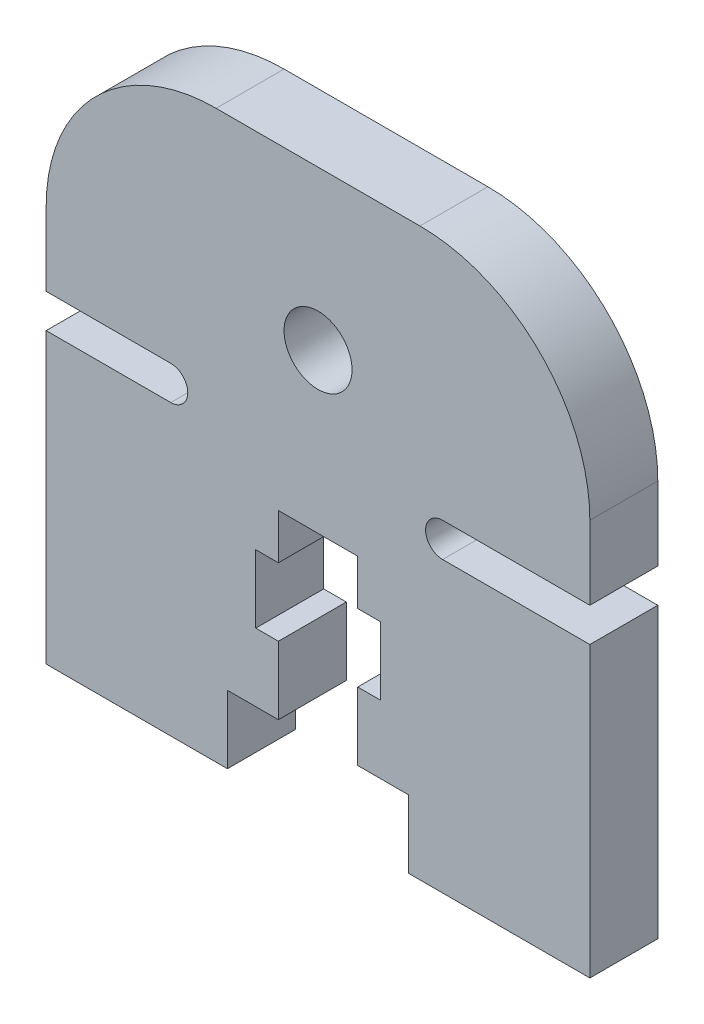
SolidWorks part; units mm, degrees
ref_plane "Plan de face" through (0, 0, 0) normal (0, 0, 1) x (1, 0, 0)
ref_plane "Plan de dessus" through (0, 0, 0) normal (0, 1, 0) x (1, 0, 0)
ref_plane "Plan de droite" through (0, 0, 0) normal (1, 0, 0) x (0, 0, -1)
sketch "Esquisse1" plane through (0, 0, 0) normal (0, 0, 1) x (1, 0, 0)
  line L1 (0, 0) -> (24, 0)
  line L2 (0, 0) -> (0, 25)
  line L3 (0, 25) -> (24, 25)
  line L4 (24, 0) -> (24, 25)
  dimension "D1" = 25
  dimension "D2" = 24
extrude "Boss.-Extru.1" add sketch "Esquisse1" along normal blind 3
fillet "Congé3" radius 7.5 2 edges at (24, 25, 1.5) (0, 25, 1.5)
sketch "Esquisse2" plane through (0, 0, 3) normal (0, 0, 1) x (1, 0, 0)
  line L0 (24, 0) -> (24, 17.5) construction
  line L1 (16.5, 25) -> (7.5, 25) construction
  circle A0 centre (12, 18) radius 1.5
  dimension "D1" = 3
  dimension "D2" = 12
  dimension "D3" = 7
extrude "Enlèv. mat.-Extru.1" cut sketch "Esquisse2" against normal up to next contours A0
sketch "Esquisse3" plane through (0, 0, 3) normal (0, 0, 1) x (1, 0, 0)
  line L0 (0, 0) -> (24, 0) construction
  line L1 (8, 0) -> (16, 0)
  line L2 (8, 0) -> (8, 3)
  line L3 (8, 3) -> (16, 3)
  line L4 (16, 0) -> (16, 3)
  dimension "D1" = 8
  dimension "D2" = 3
  dimension "D3" = 8
extrude "Enlèv. mat.-Extru.2" cut sketch "Esquisse3" against normal up to next contours L3 L4 L1 L2
sketch "Esquisse4" plane through (0, 0, 3) normal (0, 0, 1) x (1, 0, 0)
  line L0 (0, 17.5) -> (0, 0) construction
  line L1 (9.25, 9) -> (14.75, 9)
  line L2 (9.25, 9) -> (9.25, 6)
  line L3 (9.25, 6) -> (14.75, 6)
  line L4 (14.75, 9) -> (14.75, 6)
  line L5 (16.5, 25) -> (7.5, 25) construction
  point P4 (12, 6)
  dimension "D1" = 5.5
  dimension "D2" = 3
  dimension "D3" = 12
  dimension "D4" = 16
extrude "Enlèv. mat.-Extru.3" cut sketch "Esquisse4" against normal up to next
sketch "Esquisse5" plane through (0, 0, 3) normal (0, 0, 1) x (1, 0, 0)
  line L1 (10.25, 11) -> (13.75, 11)
  line L2 (10.25, 11) -> (10.25, 0)
  line L3 (10.25, 0) -> (13.75, 0)
  line L4 (13.75, 11) -> (13.75, 0)
  point P4 (12, 0)
  dimension "D1" = 12
  dimension "D2" = 11
  dimension "D3" = 3.5
extrude "Enlèv. mat.-Extru.4" cut sketch "Esquisse5" against normal up to next contours L1 L4 L3 L2
sketch "Esquisse6" plane through (0, 0, 3) normal (0, 0, 1) x (1, 0, 0)
  line L0 (17.5, 13.5) -> (30.5, 13.5) construction
  line L1 (24, 0) -> (24, 17.5) construction
  line L2 (17.5, 14.25) -> (30.5, 14.25)
  line L3 (17.5, 12.75) -> (30.5, 12.75)
  line L4 (16, 0) -> (24, 0) construction
  arc A0 (17.5, 14.25) -> (17.5, 12.75) centre (17.5, 13.5) ccw
  arc A1 (30.5, 12.75) -> (30.5, 14.25) centre (30.5, 13.5) ccw
  point P4 (24, 13.5)
  dimension "D2" = 0.75
  dimension "D1" = 6.5
  dimension "D3" = 13.5
extrude "Enlèv. mat.-Extru.5" cut sketch "Esquisse6" against normal up to next contours L2 A1 L3 A0
sketch "Esquisse7" plane through (0, 0, 3) normal (0, 0, 1) x (1, 0, 0)
  line L0 (-5.5, 13.5) -> (5.5, 13.5) construction
  line L1 (0, 17.5) -> (0, 0) construction
  line L2 (-5.5, 14.25) -> (5.5, 14.25)
  line L3 (-5.5, 12.75) -> (5.5, 12.75)
  line L4 (0, 0) -> (8, 0) construction
  arc A0 (-5.5, 14.25) -> (-5.5, 12.75) centre (-5.5, 13.5) ccw
  arc A1 (5.5, 12.75) -> (5.5, 14.25) centre (5.5, 13.5) ccw
  point P4 (0, 13.5)
  dimension "D2" = 0.75
  dimension "D1" = 5.5
  dimension "D3" = 13.5
extrude "Enlèv. mat.-Extru.6" cut sketch "Esquisse7" against normal up to next contours L2 A1 L3 A0
